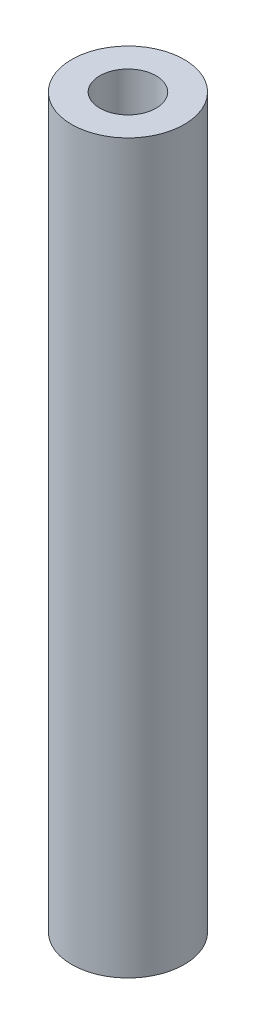
SolidWorks part; units mm, degrees
ref_plane "Front Plane" through (0, 0, 0) normal (0, 0, 1) x (1, 0, 0)
ref_plane "Top Plane" through (0, 0, 0) normal (0, 1, 0) x (1, 0, 0)
ref_plane "Right Plane" through (0, 0, 0) normal (1, 0, 0) x (0, 0, -1)
sketch "Sketch1" plane through (0, 0, 0) normal (0, 1, 0) x (1, 0, 0)
  circle A0 centre (0, 0) radius 3.175
  circle A1 centre (0, 0) radius 6.35
  dimension "D1" = 6.35
  dimension "D2" = 12.7
extrude "Boss-Extrude1" add sketch "Sketch1" along normal blind 82.042
